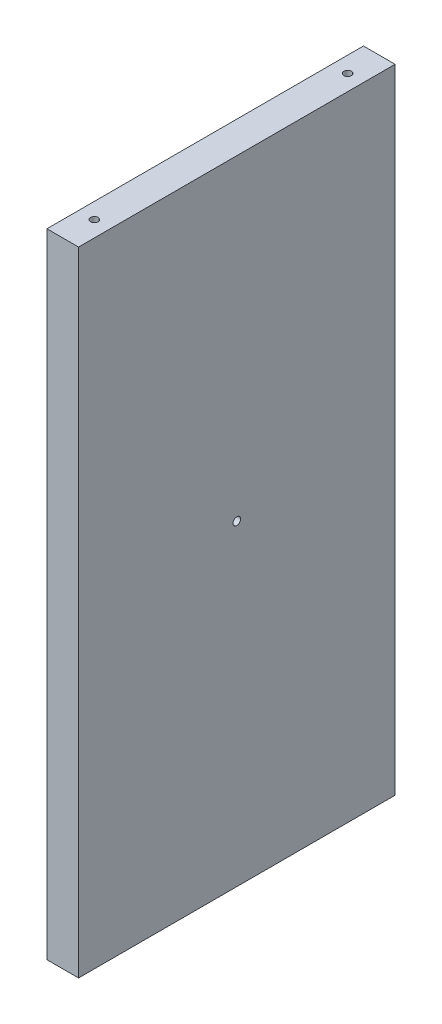
SolidWorks part; units mm, degrees
ref_plane "Front Plane" through (0, 0, 0) normal (0, 0, 1) x (1, 0, 0)
ref_plane "Top Plane" through (0, 0, 0) normal (0, 1, 0) x (1, 0, 0)
ref_plane "Right Plane" through (0, 0, 0) normal (1, 0, 0) x (0, 0, -1)
sketch "Sketch1" plane through (0, 0, 0) normal (0, 1, 0) x (1, 0, 0)
  line L1 (-5, 50) -> (5, 50)
  line L2 (-5, 50) -> (-5, -50)
  line L3 (-5, -50) -> (5, -50)
  line L4 (5, 50) -> (5, -50)
  line L5 (-5, 50) -> (5, -50) construction
  line L6 (-5, -50) -> (5, 50) construction
  point P0 (0, 0)
  dimension "D1" = 100
  dimension "D2" = 10
extrude "Boss-Extrude1" add sketch "Sketch1" along normal blind 200
hole_wizard "M2 Clearance Hole1" positions "Sketch3" profile "Sketch2" hole size "M2" standard "ANSI Metric"
sketch "Sketch3" plane through (0, 200, 0) normal (0, 1, 0) x (1, 0, 0)
  line L0 (5, 50) -> (-5, 50) construction
  point P0 (0, 40)
  point P2 (0, -40)
  dimension "D1" = 10
  dimension "D2" = 80
sketch "Sketch2" plane through (0, 200, -40) normal (1, 0, 0) x (0, 0, 1)
  line L0 (0, 0) -> (0, 11.721)
  line L1 (0, 11.721) -> (1.2, 11)
  line L2 (1.2, 11) -> (1.2, 0)
  line L5 (1.2, 0) -> (0, 0)
  line L10 (0, 11.721) -> (-1.2, 11) construction
  line L11 (0, -6.35) -> (0, 107.95) construction
  dimension "Hole Dia." = 2.4
  dimension "Hole Depth" = 11
  dimension "Drill Angle" = 118
hole_wizard "M2 Clearance Hole2" positions "Sketch5" profile "Sketch4" hole size "M2" standard "ANSI Metric"
sketch "Sketch5" plane through (0, 0, 0) normal (0, -1, 0) x (-1, 0, 0)
  line L0 (5, -50) -> (-5, -50) construction
  point P0 (0, 40)
  point P2 (0, -40)
  dimension "D1" = 10
  dimension "D2" = 80
sketch "Sketch4" plane through (0, 0, -40) normal (1, 0, 0) x (0, 0, -1)
  line L0 (0, 0) -> (0, 11.721)
  line L1 (0, 11.721) -> (1.2, 11)
  line L2 (1.2, 11) -> (1.2, 0)
  line L5 (1.2, 0) -> (0, 0)
  line L10 (0, 11.721) -> (-1.2, 11) construction
  line L11 (0, -6.35) -> (0, 107.95) construction
  dimension "Hole Dia." = 2.4
  dimension "Hole Depth" = 11
  dimension "Drill Angle" = 118
hole_wizard "M2 Clearance Hole3" positions "Sketch7" profile "Sketch6" hole size "M2" standard "ANSI Metric" end condition through all
sketch "Sketch7" plane through (-5, 0, 0) normal (-1, 0, 0) x (0, 0, 1)
  line L0 (-50, 200) -> (50, 200) construction
  point P0 (0, 100)
  dimension "D1" = 100
sketch "Sketch6" plane through (-5, 100, 0) normal (0, 1, 0) x (0, 0, 1)
  line L0 (0, 0) -> (0, 10)
  line L1 (0, 10) -> (1.2, 10)
  line L2 (1.2, 10) -> (1.2, 0)
  line L5 (1.2, 0) -> (0, 0)
  line L11 (0, -6.35) -> (0, 107.95) construction
  dimension "Thru Hole Dia." = 2.4
  dimension "Thru Hole Depth" = 10
